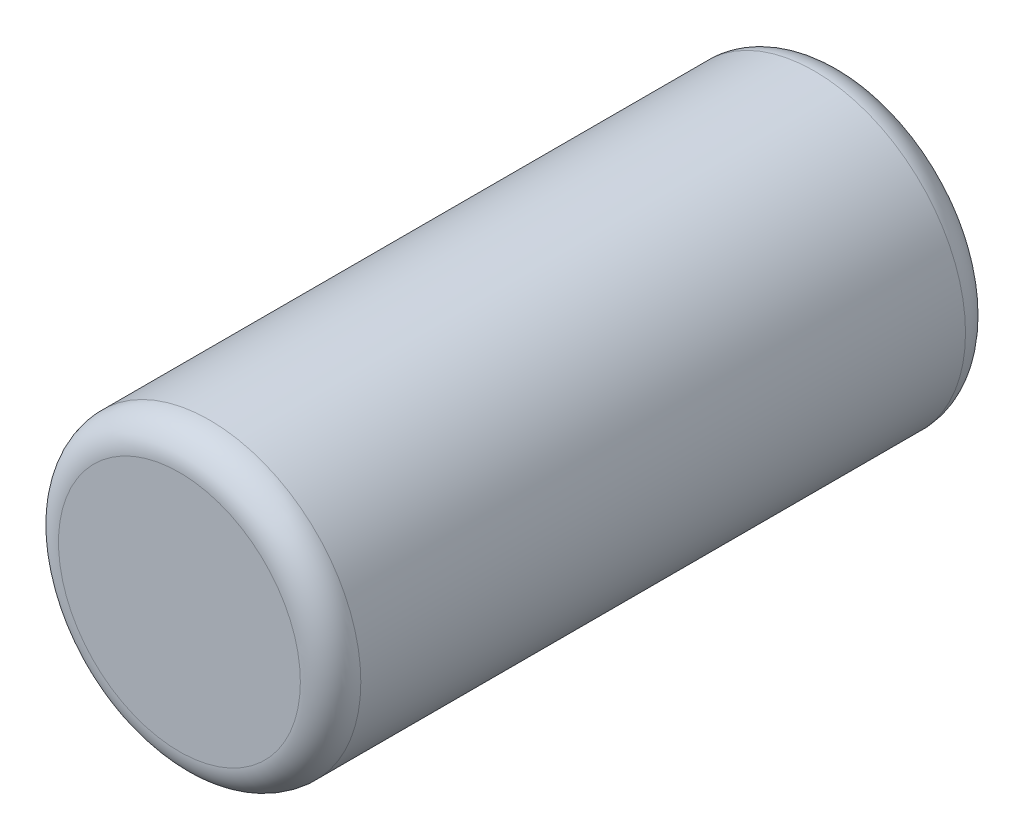
SolidWorks part; units mm, degrees
ref_plane "Front Plane" through (0, 0, 0) normal (0, 0, 1) x (1, 0, 0)
ref_plane "Top Plane" through (0, 0, 0) normal (0, 1, 0) x (1, 0, 0)
ref_plane "Right Plane" through (0, 0, 0) normal (1, 0, 0) x (0, 0, -1)
sketch "Sketch1" plane through (0, 0, 0) normal (0, 0, 1) x (1, 0, 0)
  circle A0 centre (0, 0) radius 5
extrude "Boss-Extrude1" add sketch "Sketch1" along normal blind 22
fillet "Fillet3" radius 1 2 edges at (5, 0, 22) (5, 0, 0)
